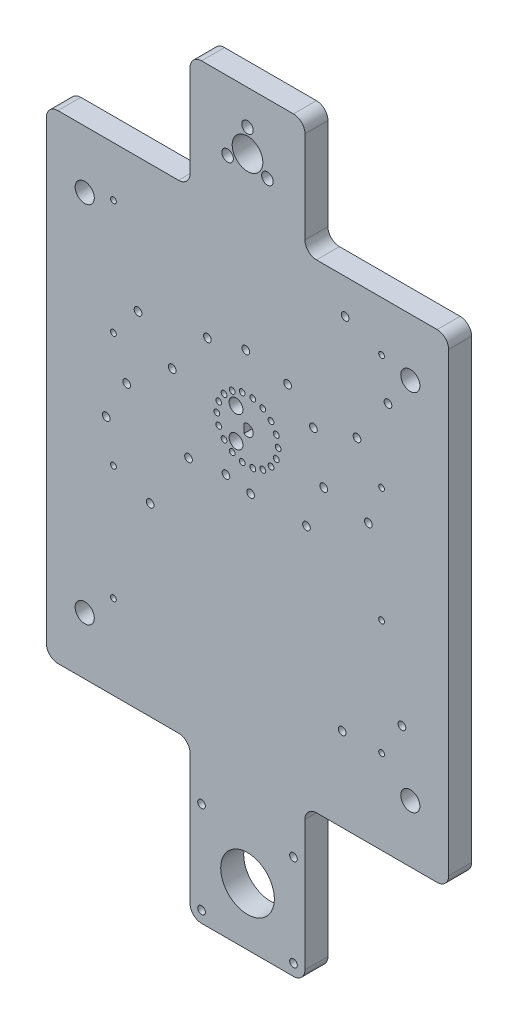
SolidWorks part; units mm, degrees
ref_plane "前视基准面" through (0, 0, 0) normal (0, 0, 1) x (1, 0, 0)
ref_plane "上视基准面" through (0, 0, 0) normal (0, 1, 0) x (1, 0, 0)
ref_plane "右视基准面" through (0, 0, 0) normal (1, 0, 0) x (0, 0, -1)
sketch "草图1" plane through (0, 0, 0) normal (0, 0, 1) x (1, 0, 0)
  line L1 (0, 0) -> (105, 0)
  line L2 (0, 0) -> (0, -125)
  line L3 (0, -125) -> (105, -125)
  line L4 (105, 0) -> (105, -125)
  dimension "D1" = 105
  dimension "D2" = 125
extrude "凸台-拉伸1" add sketch "草图1" along normal blind 6
sketch "草图2" plane through (0, 0, 6) normal (0, 0, 1) x (1, 0, 0)
  line L0 (52.5, 0) -> (52.5, -125) construction
  line L1 (105, 0) -> (0, 0) construction
  line L2 (0, -125) -> (105, -125) construction
  circle A11 centre (17.5, -13) radius 0.75
  circle A12 centre (87.5, -13) radius 0.75
  circle A13 centre (87.5, -43) radius 0.75
  circle A14 centre (87.5, -73) radius 0.75
  circle A15 centre (87.5, -103) radius 0.75
  circle A16 centre (17.5, -43) radius 0.75
  circle A17 centre (17.5, -73) radius 0.75
  circle A18 centre (17.5, -103) radius 0.75
  dimension "D8" = 1.5
  dimension "D9" = 2
  dimension "D10" = 4
extrude "切除-拉伸1" cut sketch "草图2" against normal up to next
fillet "圆角1" radius 3 4 edges at (105, -125, 3) (0, -125, 3) (0, 0, 3) (105, 0, 3)
sketch "草图3" plane through (0, 0, 6) normal (0, 0, 1) x (1, 0, 0)
  line L2 (51.6, -46.3) -> (51.6, -48.7)
  arc A6 (51.6, -48.7) -> (51.6, -46.3) centre (52.5, -47.5) ccw
  circle A7 centre (49.5, -43.5) radius 1.8
  circle A8 centre (49.5, -51.5) radius 1.8
extrude "切除-拉伸2" cut sketch "草图3" against normal up to next and the other way through all
sketch "Sketch1" plane through (0, 0, 6) normal (0, 0, 1) x (1, 0, 0)
  circle A19 centre (52.5, -47.5) radius 8 construction
  circle A20 centre (60.5, -47.5) radius 0.75
  circle A25 centre (60.0175, -50.2362) radius 0.75
  circle A26 centre (52.5, -47.5) radius 8 construction
  circle A27 centre (58.6284, -52.6423) radius 0.75
  circle A28 centre (52.5, -47.5) radius 8 construction
  circle A29 centre (56.5, -54.4282) radius 0.75
  circle A30 centre (52.5, -47.5) radius 8 construction
  circle A31 centre (53.8892, -55.3785) radius 0.75
  circle A32 centre (52.5, -47.5) radius 8 construction
  circle A33 centre (51.1108, -55.3785) radius 0.75
  circle A34 centre (52.5, -47.5) radius 8 construction
  circle A35 centre (48.5, -54.4282) radius 0.75
  circle A36 centre (52.5, -47.5) radius 8 construction
  circle A37 centre (46.3716, -52.6423) radius 0.75
  circle A38 centre (52.5, -47.5) radius 8 construction
  circle A39 centre (44.9825, -50.2362) radius 0.75
  circle A40 centre (52.5, -47.5) radius 8 construction
  circle A41 centre (44.5, -47.5) radius 0.75
  circle A42 centre (52.5, -47.5) radius 8 construction
  circle A43 centre (44.9825, -44.7638) radius 0.75
  circle A44 centre (52.5, -47.5) radius 8 construction
  circle A45 centre (46.3716, -42.3577) radius 0.75
  circle A46 centre (52.5, -47.5) radius 8 construction
  circle A47 centre (48.5, -40.5718) radius 0.75
  circle A48 centre (52.5, -47.5) radius 8 construction
  circle A49 centre (51.1108, -39.6215) radius 0.75
  circle A50 centre (52.5, -47.5) radius 8 construction
  circle A51 centre (53.8892, -39.6215) radius 0.75
  circle A52 centre (52.5, -47.5) radius 8 construction
  circle A53 centre (56.5, -40.5718) radius 0.75
  circle A54 centre (52.5, -47.5) radius 8 construction
  circle A55 centre (58.6284, -42.3577) radius 0.75
  circle A56 centre (52.5, -47.5) radius 8 construction
  circle A57 centre (60.0175, -44.7638) radius 0.75
  circle A58 centre (52.5, -47.5) radius 8 construction
  point P41 (52.5, -47.5)
  point P70 (52.5, -47.5)
  dimension "D1" = 18
extrude "Cut-Extrude1" cut sketch "Sketch1" against normal through all both
sketch "Sketch2" plane through (0, 0, 0) normal (0, 0, -1) x (-1, 0, 0)
  line L0 (-87.5, -13) -> (-53.8892, -39.6215) construction
  line L1 (-87.5, -103) -> (-58.6284, -52.6423) construction
  line L2 (-17.5, -73) -> (-44.9825, -50.2362) construction
  line L3 (-87.5, -43) -> (-60.5, -47.5) construction
  line L4 (-68.9325, -52.5201) -> (-53.3075, -61.4564) construction
  line L5 (-92.8209, -94.1859) -> (-77.2053, -103.1388) construction
  line L6 (-63.5497, -43.4482) -> (-52.0676, -29.586) construction
  line L7 (-77.9925, -9.0494) -> (-89.1685, -23.1595) construction
  line L8 (-27.0917, -76.7416) -> (-15.6096, -62.8794) construction
  line L9 (-46.8729, -60.3567) -> (-35.3908, -46.4945) construction
  line L10 (-17.5, -43) -> (-44.5, -47.5) construction
  line L11 (-68.9325, -52.5201) -> (-72.4047, -50.5342) construction
  line L12 (-84.0476, -52.6995) -> (-81.0884, -34.9444) construction
  line L13 (-62.966, -31.8821) -> (-67.898, -61.4739) construction
  line L14 (-37.102, -61.4739) -> (-42.034, -31.8821) construction
  line L15 (-23.9116, -34.9444) -> (-20.9524, -52.6995) construction
  line L16 (-35.3908, -46.4945) -> (-32.8392, -43.414) construction
  line L17 (-63.5497, -43.4482) -> (-69.7107, -38.345) construction
  circle A0 centre (-52.0676, -29.586) radius 1
  circle A2 centre (-77.9925, -9.0494) radius 1
  circle A3 centre (-89.1685, -23.1595) radius 1
  circle A4 centre (-15.6096, -62.8794) radius 1
  circle A5 centre (-27.0917, -76.7416) radius 1
  circle A7 centre (-46.8729, -60.3567) radius 1
  circle A9 centre (-53.3075, -61.4564) radius 1
  circle A10 centre (-92.8209, -94.1859) radius 1
  circle A11 centre (-77.2053, -103.1388) radius 1
  circle A12 centre (-81.0884, -34.9444) radius 1
  circle A13 centre (-84.0476, -52.6995) radius 1
  circle A18 centre (-23.9116, -34.9444) radius 1
  circle A19 centre (-20.9524, -52.6995) radius 1
  circle A20 centre (-62.966, -31.8821) radius 1
  circle A21 centre (-67.898, -61.4739) radius 1
  circle A22 centre (-42.034, -31.8821) radius 1
  circle A23 centre (-37.102, -61.4739) radius 1
  circle A25 centre (-72.4047, -50.5342) radius 1
  circle A26 centre (-32.8392, -43.414) radius 1
  circle A27 centre (-69.7107, -38.345) radius 1
  point P18 (-57.8087, -36.5171)
  point P24 (-83.5805, -16.1044)
  point P29 (-21.3506, -69.8105)
  point P33 (-41.1318, -53.4256)
  point P36 (-61.12, -56.9882)
  point P41 (-85.0131, -98.6623)
  point P54 (-82.568, -43.822)
  point P62 (-39.568, -46.678)
  point P69 (-22.432, -43.822)
  point P73 (-65.432, -46.678)
extrude "Cut-Extrude2" cut sketch "Sketch2" against normal up to next
sketch "Sketch3" plane through (0, 0, 0) normal (0, 0, -1) x (-1, 0, 0)
  line L0 (-52.5, 0) -> (-52.5, -125) construction
  line L1 (-102, 0) -> (-3, 0) construction
  line L2 (-3, -125) -> (-102, -125) construction
  line L3 (-52.5, 0) -> (-37.5, 0)
  line L4 (-37.5, 0) -> (-37.5, 30)
  line L5 (-37.5, 30) -> (-67.5, 30)
  line L6 (-67.5, 30) -> (-67.5, 0)
  line L7 (-67.5, 0) -> (-52.5, 0)
  line L8 (-52.5, -125) -> (-37.5, -125)
  line L9 (-37.5, -125) -> (-37.5, -165)
  line L10 (-37.5, -165) -> (-67.5, -165)
  line L11 (-67.5, -165) -> (-67.5, -125)
  line L12 (-67.5, -125) -> (-52.5, -125)
extrude "Boss-Extrude1" add sketch "Sketch3" against normal blind 6
sketch "Sketch4" plane through (0, 0, 0) normal (0, 0, -1) x (-1, 0, 0)
  circle A0 centre (-52.5, 15) radius 10 construction
  circle A1 centre (-52.5, 15) radius 4
  circle A2 centre (-52.5, 21) radius 1.5
  circle A3 centre (-47.3038, 12) radius 1.5
  circle A4 centre (-57.6962, 12) radius 1.5
  point P11 (-52.5, 15)
  dimension "D1" = 6
extrude "Cut-Extrude3" cut sketch "Sketch4" against normal up to next
fillet "Fillet1" radius 3 4 edges at (37.5, 0, 3) (37.5, 30, 3) (67.5, 30, 3) (67.5, 0, 3)
sketch "Sketch5" plane through (0, 0, 0) normal (0, 0, -1) x (-1, 0, 0)
  line L0 (-102, 0) -> (-70.5, 0) construction
  line L1 (-105, -122) -> (-105, -3) construction
  line L2 (-3, -125) -> (-37.5, -125) construction
  line L3 (0, -3) -> (0, -122) construction
  circle A0 centre (-95, -15) radius 2.5
  circle A1 centre (-95, -110) radius 2.5
  circle A2 centre (-10, -15) radius 2.5
  circle A3 centre (-10, -110) radius 2.5
  dimension "D1" = 15
  dimension "D3" = 15
  dimension "D4" = 10
  dimension "D2" = 10
extrude "Cut-Extrude4" cut sketch "Sketch5" against normal up to next
sketch "Sketch6" plane through (0, 0, 0) normal (0, 0, -1) x (-1, 0, 0)
  line L0 (-67.5, -125) -> (-67.5, -165) construction
  line L1 (-67.5, -125) -> (-102, -125) construction
  line L2 (-37.5, -165) -> (-37.5, -125) construction
  line L3 (-67.5, -165) -> (-37.5, -165) construction
  circle A0 centre (-64.5, -138) radius 1
  circle A1 centre (-40.5, -138) radius 1
  circle A2 centre (-64.5, -162) radius 1
  circle A3 centre (-40.5, -162) radius 1
  circle A4 centre (-52.5, -150) radius 7
  dimension "D1" = 3
  dimension "D3" = 3
  dimension "D4" = 3
  dimension "D5" = 15
  dimension "D2" = 13
  dimension "D6" = 15
extrude "Cut-Extrude5" cut sketch "Sketch6" against normal up to next
fillet "Fillet2" radius 3 4 edges at (37.5, -125, 3) (37.5, -165, 3) (67.5, -165, 3) (67.5, -125, 3)
